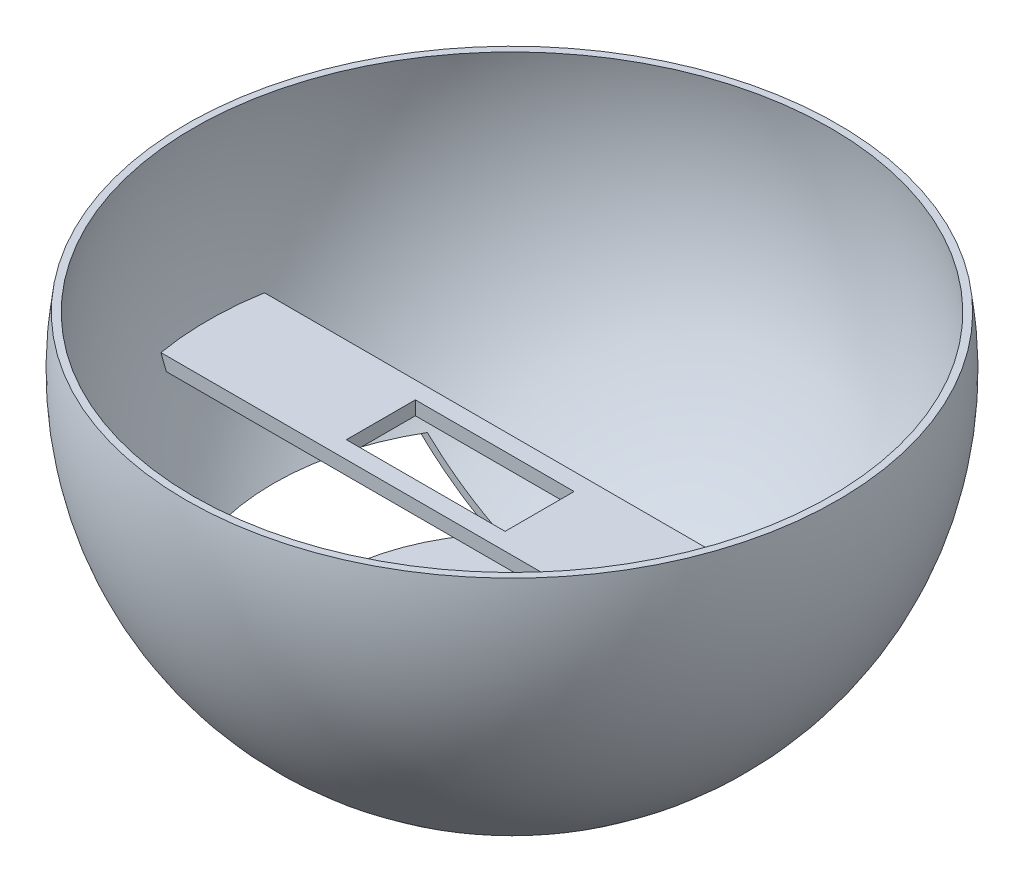
SolidWorks part; units mm, degrees
ref_plane "前视基准面" through (0, 0, 0) normal (0, 0, 1) x (1, 0, 0)
ref_plane "上视基准面" through (0, 0, 0) normal (0, 1, 0) x (1, 0, 0)
ref_plane "右视基准面" through (0, 0, 0) normal (1, 0, 0) x (0, 0, -1)
sketch "草图1" plane through (0, 0, 0) normal (1, 0, 0) x (0, 0, -1)
  line L0 (-47.2007, 7.2217) -> (0, 7.2217)
  line L1 (0, 7.2217) -> (0, -40.5137)
  line L2 (0, -40.5137) -> (-25.2725, -40.5137)
  arc A0 (-47.2007, 7.2217) -> (-25.2725, -40.5137) centre (0, 0) ccw
  dimension "D1" = 95.5
revolve "旋转1" add sketch "草图1" angle 360 about L1
shell "抽壳1" thickness 1
ref_plane "基准面1" through (0, -12.7783, 0) normal (0, 1, 0) x (1, 0, 0)
sketch "草图2" plane through (0, 0, 0) normal (1, 0, 0) x (0, 0, -1)
  line L0 (0, -15.7783) -> (0, 0) construction
  line L1 (-7.5, -15.7783) -> (7.5, -15.7783)
  line L2 (-7.5, -15.7783) -> (-7.5, -17.7783)
  line L3 (-7.5, -17.7783) -> (7.5, -17.7783)
  line L4 (7.5, -15.7783) -> (7.5, -17.7783)
  line L5 (-7.5, -15.7783) -> (0, 0) construction
  line L6 (0, 0) -> (7.5, -15.7783) construction
  line L7 (51.9208, -12.7783) -> (-51.9208, -12.7783) construction
  dimension "D1" = 15
  dimension "D2" = 2
  dimension "D3" = 5
extrude "凸台-拉伸1" add sketch "草图2" along normal up to next
sketch "草图4" plane through (0, 0, 0) normal (1, 0, 0) x (0, 0, -1)
  line L0 (0, -15.7783) -> (0, 0) construction
  line L1 (-7.5, -15.7783) -> (7.5, -15.7783)
  line L2 (-7.5, -15.7783) -> (-7.5, -17.7783)
  line L3 (-7.5, -17.7783) -> (7.5, -17.7783)
  line L4 (7.5, -15.7783) -> (7.5, -17.7783)
  line L5 (-7.5, -15.7783) -> (0, 0) construction
  line L6 (0, 0) -> (7.5, -15.7783) construction
  line L7 (51.9208, -12.7783) -> (-51.9208, -12.7783) construction
  dimension "D1" = 15
  dimension "D2" = 2
  dimension "D3" = 5
extrude "凸台-拉伸2" add sketch "草图4" against normal up to next
sketch "草图5" plane through (0, -15.7783, 0) normal (0, 1, 0) x (1, 0, 0)
  line L0 (0, 0) -> (0, -5) construction
  line L1 (4, -5) -> (-19, -5)
  line L2 (4, -5) -> (4, 5)
  line L3 (4, 5) -> (-19, 5)
  line L4 (-19, -5) -> (-19, 5)
  line L5 (0, -26.2545) -> (0, 26.2545) construction
  line L6 (0, 0) -> (0, 5) construction
  dimension "D1" = 10
  dimension "D2" = 4
  dimension "D3" = 23
extrude "切除-拉伸1" cut sketch "草图5" against normal blind 10
sketch "草图6" plane through (0, 0, 0) normal (1, 0, 0) x (0, 0, -1)
  line L0 (0, 0) -> (0, -31.5137) construction
  line L1 (17.5, -31.5137) -> (-17.5, -31.5137)
  line L2 (17.5, -31.5137) -> (17.5, -39.5137)
  line L3 (17.5, -39.5137) -> (-17.5, -39.5137)
  line L4 (-17.5, -31.5137) -> (-17.5, -39.5137)
  line L6 (-25.2725, -40.5137) -> (25.2725, -40.5137) construction
  dimension "D1" = 35
  dimension "D2" = 8
  dimension "D3" = 1
extrude "切除-拉伸2" cut sketch "草图6" against normal blind 47
